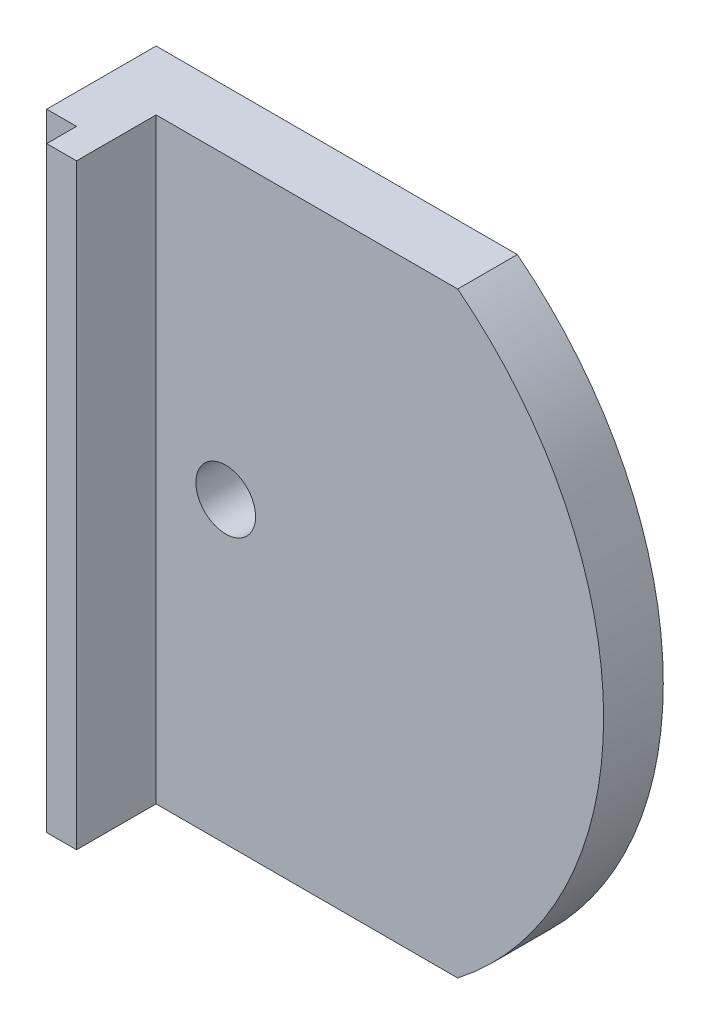
SolidWorks part; units mm, degrees
material "ABS"
ref_plane "Plan de face" through (0, 0, 0) normal (0, 0, 1) x (1, 0, 0)
ref_plane "Plan de dessus" through (0, 0, 0) normal (0, 1, 0) x (1, 0, 0)
ref_plane "Plan de droite" through (0, 0, 0) normal (1, 0, 0) x (0, 0, -1)
sketch "Esquisse1" plane through (0, 0, 0) normal (0, 1, 0) x (1, 0, 0)
  line L0 (0, -7) -> (0, 0)
  line L1 (0, 0) -> (27, 0)
  dimension "D1" = 27
  dimension "D2" = 7
extrude "Extru.-Mince1" add sketch "Esquisse1" along normal mid plane 30 thin
sketch "Esquisse2" plane through (0, 0, 3) normal (0, 0, 1) x (1, 0, 0)
  line L1 (3, 15) -> (3, -15) construction
  line L6 (3, -15) -> (27, -15)
  line L7 (27, -15) -> (27, 15)
  line L8 (27, 15) -> (3, 15)
  line L9 (3, 15) -> (3, -15)
  line L10 (18.1619, -15) -> (27, -15)
  line L11 (27, -15) -> (27, 15)
  line L12 (27, 15) -> (18.1619, 15)
  circle A0 centre (6.5, 0) radius 1.5
  arc A1 (18.1619, -15) -> (18.1619, 15) centre (6.5, 0) ccw
  dimension "D1" = 3.5
  dimension "D2" = 3
  dimension "D4" = 19
  dimension "D3" = 0
extrude "Enlèv. mat.-Extru.1" cut sketch "Esquisse2" against normal through all
sketch "Esquisse3" plane through (0, 15, 0) normal (0, 1, 0) x (1, 0, 0)
  line L0 (3, -7) -> (0, -7) construction
  line L1 (1.5, -7) -> (0, -7)
  line L2 (1.5, -7) -> (1.5, -5.5)
  line L3 (1.5, -5.5) -> (0, -5.5)
  line L4 (0, -7) -> (0, -5.5)
  line L5 (0, -7) -> (0, 0) construction
extrude "Enlèv. mat.-Extru.2" cut sketch "Esquisse3" against normal through all
sketch "Esquisse4" plane through (0, 0, 0) normal (0, 0, -1) x (-1, 0, 0)
  circle A0 centre (-6.5, 0) radius 6
  circle A1 centre (-6.5, 0) radius 1.5
  circle A2 centre (-6.5, 0) radius 1.5 construction
  dimension "D1" = 12
extrude "Boss.-Extru.1" add sketch "Esquisse4" along normal blind 2
